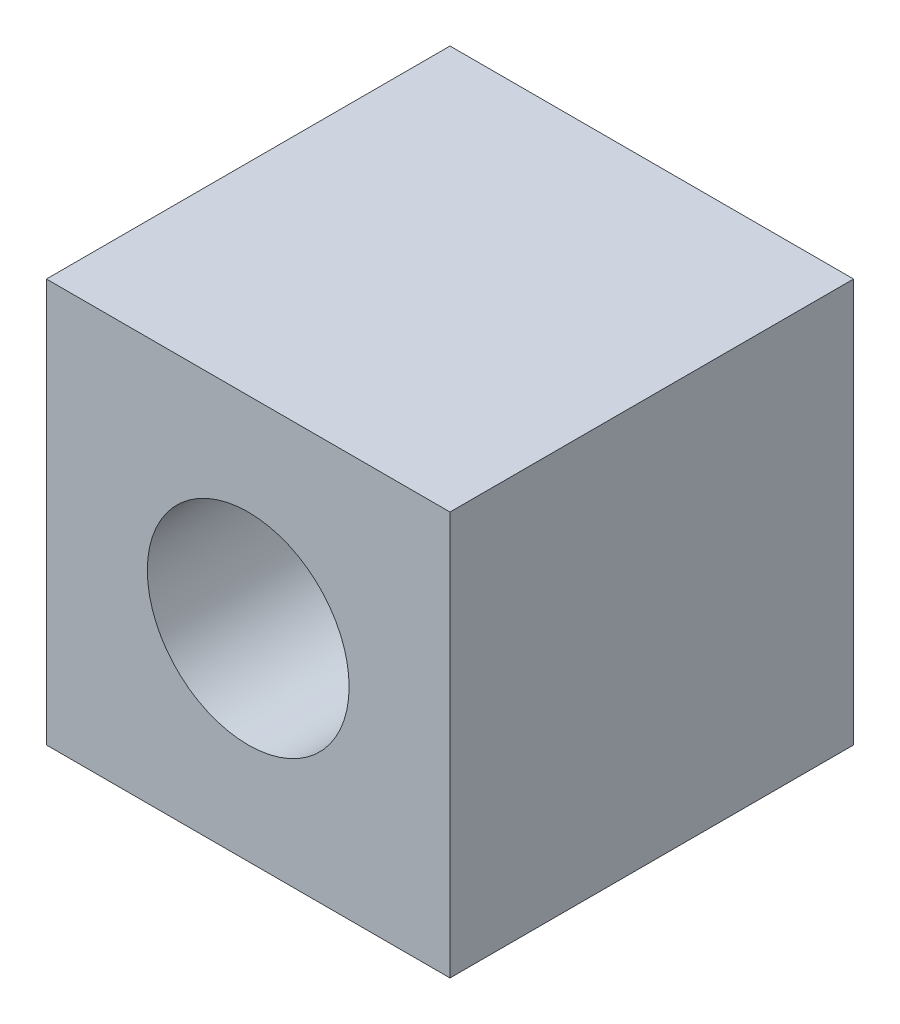
SolidWorks part; units mm, degrees
ref_plane "Front Plane" through (0, 0, 0) normal (0, 0, 1) x (1, 0, 0)
ref_plane "Top Plane" through (0, 0, 0) normal (0, 1, 0) x (1, 0, 0)
ref_plane "Right Plane" through (0, 0, 0) normal (1, 0, 0) x (0, 0, -1)
sketch "Sketch1" plane through (0, 0, 0) normal (0, 0, 1) x (1, 0, 0)
  line L1 (0, 0) -> (10, 0)
  line L2 (0, 0) -> (0, 10)
  line L3 (0, 10) -> (10, 10)
  line L4 (10, 0) -> (10, 10)
extrude "Boss-Extrude1" add sketch "Sketch1" along normal blind 10
sketch "Sketch2" plane through (0, 0, 0) normal (0, 0, 1) x (1, 0, 0)
  circle A0 centre (5, 5) radius 2.5
extrude "Cut-Extrude1" cut sketch "Sketch2" along normal through all
